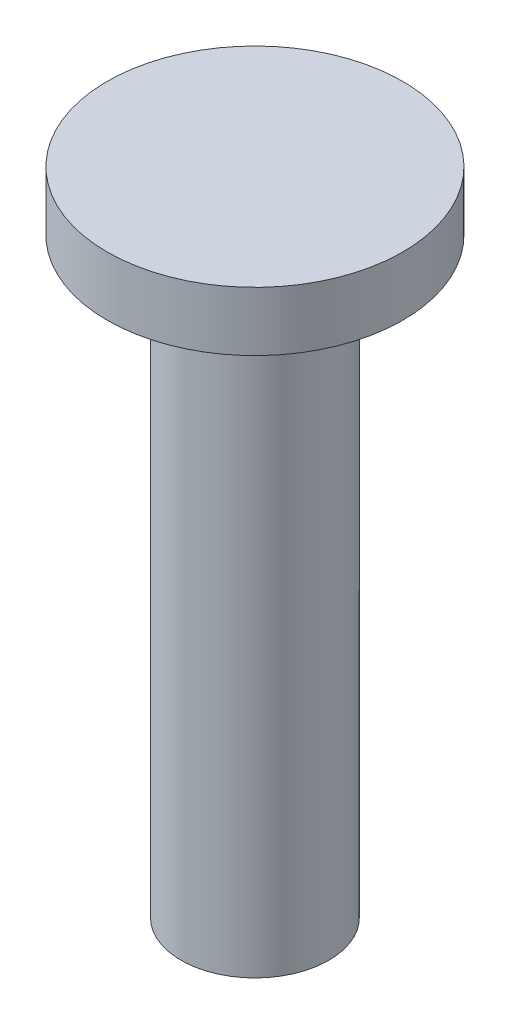
SolidWorks part; units mm, degrees
material "AISI 304"
ref_plane "前视基准面" through (0, 0, 0) normal (0, 0, 1) x (1, 0, 0)
ref_plane "上视基准面" through (0, 0, 0) normal (0, 1, 0) x (1, 0, 0)
ref_plane "右视基准面" through (0, 0, 0) normal (1, 0, 0) x (0, 0, -1)
other "Configuration Table"
sketch "草图1" plane through (0, 0, 0) normal (0, 1, 0) x (1, 0, 0)
  circle A0 centre (0, 0) radius 2
  dimension "D1" = 4
extrude "凸台-拉伸1" add sketch "草图1" along normal blind 0.8
sketch "草图2" plane through (0, 0, 0) normal (0, -1, 0) x (1, 0, 0)
  circle A0 centre (0, 0) radius 1
  dimension "D1" = 2
extrude "凸台-拉伸2" add sketch "草图2" along normal blind 8
